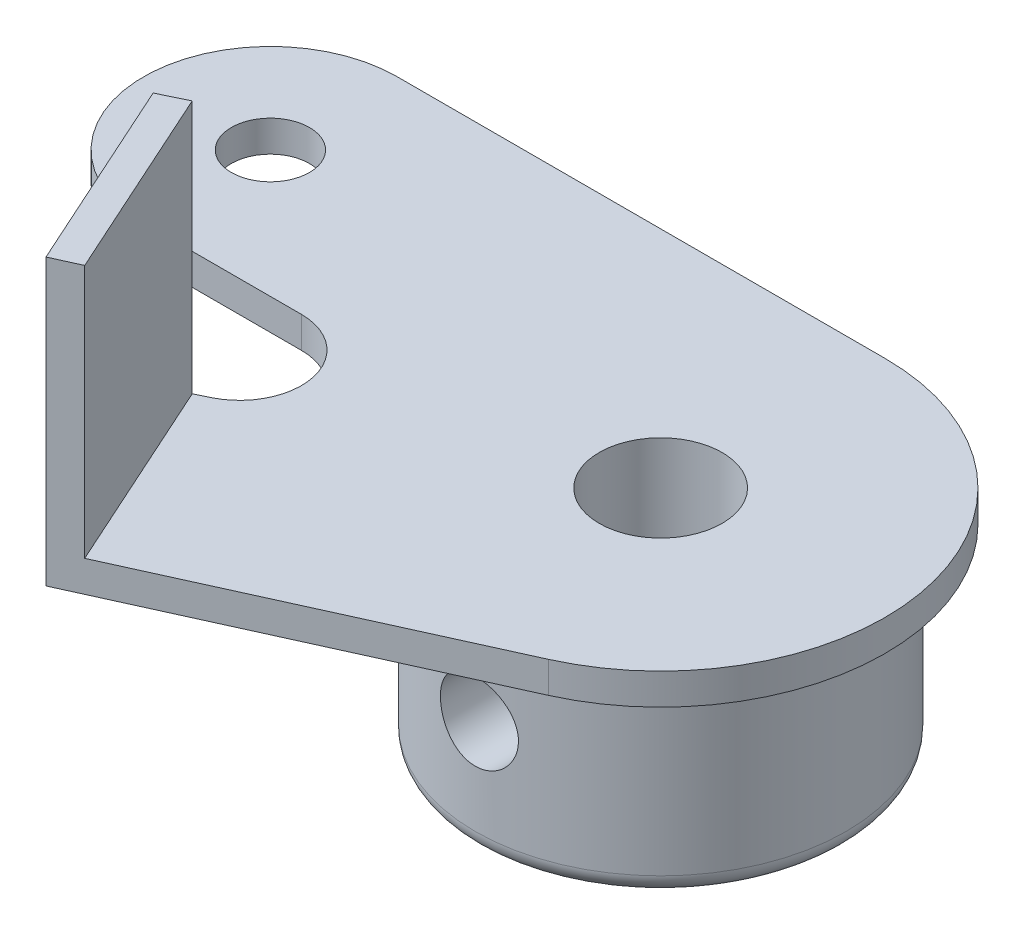
SolidWorks part; units mm, degrees
material "AISI 1020"
ref_plane "Plan de face" through (0, 0, 0) normal (0, 0, 1) x (1, 0, 0)
ref_plane "Plan de dessus" through (0, 0, 0) normal (0, 1, 0) x (1, 0, 0)
ref_plane "Plan de droite" through (0, 0, 0) normal (1, 0, 0) x (0, 0, -1)
sketch "Esquisse1" plane through (0, 0, 0) normal (0, 1, 0) x (1, 0, 0)
  line L0 (0, 11.5) -> (-25, 11.5)
  line L1 (-15.5325, -7.5102) -> (-17.5325, -8.4772)
  line L2 (-25, -1.5) -> (-16.9092, -1.5)
  line L3 (4.7385, -10.4784) -> (-13, -18.5)
  line L4 (-17.5325, -8.4772) -> (-13, -18.5)
  arc A0 (4.7385, -10.4784) -> (0, 11.5) centre (0, 0) ccw
  arc A1 (-25, 11.5) -> (-25, -1.5) centre (-25, 5) ccw
  arc A2 (-16.9092, -1.5) -> (-15.5325, -7.5102) centre (-16.9092, -4.6628) cw
  circle A3 centre (0, 0) radius 3.15
  circle A4 centre (-25, 5) radius 2
  point P10 (11.5, 0)
  point P11 (-31.5, 5)
  dimension "D1" = 23
  dimension "D2" = 6.5
  dimension "D8" = 6.3
  dimension "D9" = 4
  dimension "D3" = 43
  dimension "D4" = 13
  dimension "D5" = 30
  dimension "D6" = 2
extrude "Boss.-Extru.1" add sketch "Esquisse1" along normal blind 1.6
sketch "Esquisse2" plane through (0, 1.6, 0) normal (0, 1, 0) x (1, 0, 0)
  circle A0 centre (0, 0) radius 9.5
  circle A1 centre (0, 0) radius 3.15
  dimension "D1" = 19
extrude "Boss.-Extru.2" add sketch "Esquisse2" against normal blind 11.5
fillet "Congé1" radius 1 1 edges at (0, -9.9, 9.5)
sketch "Esquisse3" plane through (0, 1.6, 0) normal (0, 1, 0) x (1, 0, 0)
  line L0 (-17.5325, -8.4772) -> (-13, -18.5)
  line L1 (-13, -18.5) -> (-11.6337, -17.8821)
  line L2 (-16.182, -7.8242) -> (-11.6337, -17.8821)
  line L3 (-13, -18.5) -> (4.7385, -10.4784) construction
  line L4 (-15.5325, -7.5102) -> (-17.5325, -8.4772) construction
  line L5 (-16.182, -7.8242) -> (-17.5325, -8.4772)
  dimension "D1" = 1.5
extrude "Boss.-Extru.3" add sketch "Esquisse3" along normal blind 13
sketch "Esquisse4" plane through (0, 0, 0) normal (0, 0, 1) x (1, 0, 0)
  circle A0 centre (0, -4) radius 2
  dimension "D1" = 4
  dimension "D2" = 4
extrude "Enlèv. mat.-Extru.1" cut sketch "Esquisse4" along normal through all
